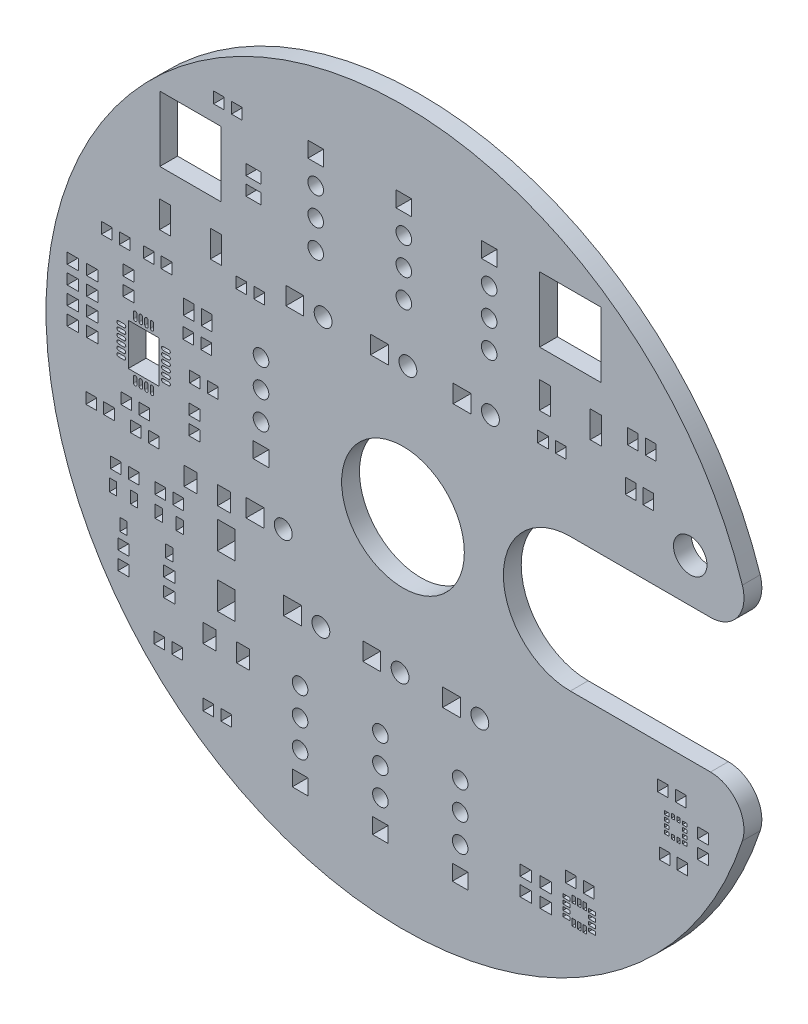
SolidWorks part; units mm, degrees
ref_plane "Plan de face" through (0, 0, 0) normal (0, 0, 1) x (1, 0, 0)
ref_plane "Plan de dessus" through (0, 0, 0) normal (0, 1, 0) x (1, 0, 0)
ref_plane "Plan de droite" through (0, 0, 0) normal (1, 0, 0) x (0, 0, -1)
sketch "Model" plane through (0, 0, 0) normal (0, 0, 1) x (1, 0, 0)
  line L0 (25.45, -12.55) -> (25.45, -12.85)
  line L1 (25.45, -12.85) -> (25.05, -12.85)
  line L2 (25.05, -12.85) -> (25.05, -12.55)
  line L3 (25.05, -12.55) -> (25.45, -12.55)
  line L4 (25.45, -12.05) -> (25.45, -12.35)
  line L5 (25.45, -12.35) -> (25.05, -12.35)
  line L6 (25.05, -12.35) -> (25.05, -12.05)
  line L7 (25.05, -12.05) -> (25.45, -12.05)
  line L8 (25.45, -11.55) -> (25.45, -11.85)
  line L9 (25.45, -11.85) -> (25.05, -11.85)
  line L10 (25.05, -11.85) -> (25.05, -11.55)
  line L11 (25.05, -11.55) -> (25.45, -11.55)
  line L12 (25.45, -11.05) -> (25.45, -11.35)
  line L13 (25.45, -11.35) -> (25.05, -11.35)
  line L14 (25.05, -11.35) -> (25.05, -11.05)
  line L15 (25.05, -11.05) -> (25.45, -11.05)
  line L16 (24.55, -10.95) -> (24.85, -10.95)
  line L17 (24.85, -10.95) -> (24.85, -11.35)
  line L18 (24.85, -11.35) -> (24.55, -11.35)
  line L19 (24.55, -11.35) -> (24.55, -10.95)
  line L20 (24.05, -10.95) -> (24.35, -10.95)
  line L21 (24.35, -10.95) -> (24.35, -11.35)
  line L22 (24.35, -11.35) -> (24.05, -11.35)
  line L23 (24.05, -11.35) -> (24.05, -10.95)
  line L24 (23.85, -11.05) -> (23.85, -11.35)
  line L25 (23.85, -11.35) -> (23.45, -11.35)
  line L26 (23.45, -11.35) -> (23.45, -11.05)
  line L27 (23.45, -11.05) -> (23.85, -11.05)
  line L28 (23.85, -11.55) -> (23.85, -11.85)
  line L29 (23.85, -11.85) -> (23.45, -11.85)
  line L30 (23.45, -11.85) -> (23.45, -11.55)
  line L31 (23.45, -11.55) -> (23.85, -11.55)
  line L32 (23.85, -12.05) -> (23.85, -12.35)
  line L33 (23.85, -12.35) -> (23.45, -12.35)
  line L34 (23.45, -12.35) -> (23.45, -12.05)
  line L35 (23.45, -12.05) -> (23.85, -12.05)
  line L36 (23.85, -12.55) -> (23.85, -12.85)
  line L37 (23.85, -12.85) -> (23.45, -12.85)
  line L38 (23.45, -12.85) -> (23.45, -12.55)
  line L39 (23.45, -12.55) -> (23.85, -12.55)
  line L40 (24.05, -12.55) -> (24.35, -12.55)
  line L41 (24.35, -12.55) -> (24.35, -12.95)
  line L42 (24.35, -12.95) -> (24.05, -12.95)
  line L43 (24.05, -12.95) -> (24.05, -12.55)
  line L44 (24.55, -12.55) -> (24.85, -12.55)
  line L45 (24.85, -12.55) -> (24.85, -12.95)
  line L46 (24.85, -12.95) -> (24.55, -12.95)
  line L47 (24.55, -12.95) -> (24.55, -12.55)
  line L48 (17.25, -23.55) -> (17.25, -23.85)
  line L49 (17.25, -23.85) -> (16.65, -23.85)
  line L50 (16.65, -23.85) -> (16.65, -23.55)
  line L51 (16.65, -23.55) -> (17.25, -23.55)
  line L52 (17.25, -23.05) -> (17.25, -23.35)
  line L53 (17.25, -23.35) -> (16.65, -23.35)
  line L54 (16.65, -23.35) -> (16.65, -23.05)
  line L55 (16.65, -23.05) -> (17.25, -23.05)
  line L56 (17.25, -22.55) -> (17.25, -22.85)
  line L57 (17.25, -22.85) -> (16.65, -22.85)
  line L58 (16.65, -22.85) -> (16.65, -22.55)
  line L59 (16.65, -22.55) -> (17.25, -22.55)
  line L60 (17.25, -22.05) -> (17.25, -22.35)
  line L61 (17.25, -22.35) -> (16.65, -22.35)
  line L62 (16.65, -22.35) -> (16.65, -22.05)
  line L63 (16.65, -22.05) -> (17.25, -22.05)
  line L64 (16.15, -21.75) -> (16.45, -21.75)
  line L65 (16.45, -21.75) -> (16.45, -22.35)
  line L66 (16.45, -22.35) -> (16.15, -22.35)
  line L67 (16.15, -22.35) -> (16.15, -21.75)
  line L68 (15.65, -21.75) -> (15.95, -21.75)
  line L69 (15.95, -21.75) -> (15.95, -22.35)
  line L70 (15.95, -22.35) -> (15.65, -22.35)
  line L71 (15.65, -22.35) -> (15.65, -21.75)
  line L72 (15.15, -21.75) -> (15.45, -21.75)
  line L73 (15.45, -21.75) -> (15.45, -22.35)
  line L74 (15.45, -22.35) -> (15.15, -22.35)
  line L75 (15.15, -22.35) -> (15.15, -21.75)
  line L76 (14.95, -22.05) -> (14.95, -22.35)
  line L77 (14.95, -22.35) -> (14.35, -22.35)
  line L78 (14.35, -22.35) -> (14.35, -22.05)
  line L79 (14.35, -22.05) -> (14.95, -22.05)
  line L80 (14.95, -22.55) -> (14.95, -22.85)
  line L81 (14.95, -22.85) -> (14.35, -22.85)
  line L82 (14.35, -22.85) -> (14.35, -22.55)
  line L83 (14.35, -22.55) -> (14.95, -22.55)
  line L84 (14.95, -23.05) -> (14.95, -23.35)
  line L85 (14.95, -23.35) -> (14.35, -23.35)
  line L86 (14.35, -23.35) -> (14.35, -23.05)
  line L87 (14.35, -23.05) -> (14.95, -23.05)
  line L88 (14.95, -23.55) -> (14.95, -23.85)
  line L89 (14.95, -23.85) -> (14.35, -23.85)
  line L90 (14.35, -23.85) -> (14.35, -23.55)
  line L91 (14.35, -23.55) -> (14.95, -23.55)
  line L92 (15.15, -23.55) -> (15.45, -23.55)
  line L93 (15.45, -23.55) -> (15.45, -24.15)
  line L94 (15.45, -24.15) -> (15.15, -24.15)
  line L95 (15.15, -24.15) -> (15.15, -23.55)
  line L96 (15.65, -23.55) -> (15.95, -23.55)
  line L97 (15.95, -23.55) -> (15.95, -24.15)
  line L98 (15.95, -24.15) -> (15.65, -24.15)
  line L99 (15.65, -24.15) -> (15.65, -23.55)
  line L100 (16.15, -23.55) -> (16.45, -23.55)
  line L101 (16.45, -23.55) -> (16.45, -24.15)
  line L102 (16.45, -24.15) -> (16.15, -24.15)
  line L103 (16.15, -24.15) -> (16.15, -23.55)
  line L104 (-18.075, 7.175) -> (-17.125, 7.175)
  line L105 (-17.125, 7.175) -> (-17.125, 5.825)
  line L106 (-17.125, 5.825) -> (-18.075, 5.825)
  line L107 (-18.075, 5.825) -> (-18.075, 7.175)
  line L108 (-19.675, 7.175) -> (-18.725, 7.175)
  line L109 (-18.725, 7.175) -> (-18.725, 5.825)
  line L110 (-18.725, 5.825) -> (-19.675, 5.825)
  line L111 (-19.675, 5.825) -> (-19.675, 7.175)
  line L112 (-21.5, 0) -> (-21, 0)
  line L113 (-21, -0.3) -> (-21.5, -0.3)
  line L114 (-21.5, 0.5) -> (-21, 0.5)
  line L115 (-21, 0.2) -> (-21.5, 0.2)
  line L116 (-21.5, 1) -> (-21, 1)
  line L117 (-21, 0.7) -> (-21.5, 0.7)
  line L118 (-21.5, 1.5) -> (-21, 1.5)
  line L119 (-21, 1.2) -> (-21.5, 1.2)
  line L120 (-21.5, 2) -> (-21, 2)
  line L121 (-21, 1.7) -> (-21.5, 1.7)
  line L122 (-21.5, 2.5) -> (-21, 2.5)
  line L123 (-21, 2.2) -> (-21.5, 2.2)
  line L124 (-22.65, 3.35) -> (-22.65, 3.85)
  line L125 (-22.35, 3.85) -> (-22.35, 3.35)
  line L126 (-23.15, 3.35) -> (-23.15, 3.85)
  line L127 (-22.85, 3.85) -> (-22.85, 3.35)
  line L128 (-23.65, 3.35) -> (-23.65, 3.85)
  line L129 (-23.35, 3.85) -> (-23.35, 3.35)
  line L130 (-24.15, 3.35) -> (-24.15, 3.85)
  line L131 (-23.85, 3.85) -> (-23.85, 3.35)
  line L132 (-25.5, 2.5) -> (-25, 2.5)
  line L133 (-25, 2.2) -> (-25.5, 2.2)
  line L134 (-25.5, 2) -> (-25, 2)
  line L135 (-25, 1.7) -> (-25.5, 1.7)
  line L136 (-25.5, 1.5) -> (-25, 1.5)
  line L137 (-25, 1.2) -> (-25.5, 1.2)
  line L138 (-25.5, 1) -> (-25, 1)
  line L139 (-25, 0.7) -> (-25.5, 0.7)
  line L140 (-25.5, 0.5) -> (-25, 0.5)
  line L141 (-25, 0.2) -> (-25.5, 0.2)
  line L142 (-25.5, 0) -> (-25, 0)
  line L143 (-25, -0.3) -> (-25.5, -0.3)
  line L144 (-24.15, -1.65) -> (-24.15, -1.15)
  line L145 (-23.85, -1.15) -> (-23.85, -1.65)
  line L146 (-23.65, -1.65) -> (-23.65, -1.15)
  line L147 (-23.35, -1.15) -> (-23.35, -1.65)
  line L148 (-23.15, -1.65) -> (-23.15, -1.15)
  line L149 (-22.85, -1.15) -> (-22.85, -1.65)
  line L150 (-22.65, -1.65) -> (-22.65, -1.15)
  line L151 (-22.35, -1.15) -> (-22.35, -1.65)
  line L152 (-21.875, 2.975) -> (-21.875, -0.775)
  line L153 (-21.875, -0.775) -> (-24.625, -0.775)
  line L154 (-24.625, -0.775) -> (-24.625, 2.975)
  line L155 (-24.625, 2.975) -> (-21.875, 2.975)
  line L156 (-24.425, -10.1) -> (-23.775, -10.1)
  line L157 (-23.775, -10.1) -> (-23.775, -11.2)
  line L158 (-23.775, -11.2) -> (-24.425, -11.2)
  line L159 (-24.425, -11.2) -> (-24.425, -10.1)
  line L160 (-26.325, -10.1) -> (-25.675, -10.1)
  line L161 (-25.675, -10.1) -> (-25.675, -11.2)
  line L162 (-25.675, -11.2) -> (-26.325, -11.2)
  line L163 (-26.325, -11.2) -> (-26.325, -10.1)
  line L164 (-25.375, -12.7) -> (-24.725, -12.7)
  line L165 (-24.725, -12.7) -> (-24.725, -13.8)
  line L166 (-24.725, -13.8) -> (-25.375, -13.8)
  line L167 (-25.375, -13.8) -> (-25.375, -12.7)
  line L168 (-20.325, -10.1) -> (-19.675, -10.1)
  line L169 (-19.675, -10.1) -> (-19.675, -11.2)
  line L170 (-19.675, -11.2) -> (-20.325, -11.2)
  line L171 (-20.325, -11.2) -> (-20.325, -10.1)
  line L172 (-22.225, -10.1) -> (-21.575, -10.1)
  line L173 (-21.575, -10.1) -> (-21.575, -11.2)
  line L174 (-21.575, -11.2) -> (-22.225, -11.2)
  line L175 (-22.225, -11.2) -> (-22.225, -10.1)
  line L176 (-21.275, -12.7) -> (-20.625, -12.7)
  line L177 (-20.625, -12.7) -> (-20.625, -13.8)
  line L178 (-20.625, -13.8) -> (-21.275, -13.8)
  line L179 (-21.275, -13.8) -> (-21.275, -12.7)
  line L180 (21.525, 13.075) -> (22.475, 13.075)
  line L181 (22.475, 13.075) -> (22.475, 11.725)
  line L182 (22.475, 11.725) -> (21.525, 11.725)
  line L183 (21.525, 11.725) -> (21.525, 13.075)
  line L184 (19.925, 13.075) -> (20.875, 13.075)
  line L185 (20.875, 13.075) -> (20.875, 11.725)
  line L186 (20.875, 11.725) -> (19.925, 11.725)
  line L187 (19.925, 11.725) -> (19.925, 13.075)
  line L188 (-14.075, 19.475) -> (-14.075, 20.425)
  line L189 (-14.075, 20.425) -> (-12.725, 20.425)
  line L190 (-12.725, 20.425) -> (-12.725, 19.475)
  line L191 (-12.725, 19.475) -> (-14.075, 19.475)
  line L192 (-14.075, 17.875) -> (-14.075, 18.825)
  line L193 (-14.075, 18.825) -> (-12.725, 18.825)
  line L194 (-12.725, 18.825) -> (-12.725, 17.875)
  line L195 (-12.725, 17.875) -> (-14.075, 17.875)
  line L196 (21.075, 15.675) -> (20.125, 15.675)
  line L197 (20.125, 15.675) -> (20.125, 17.025)
  line L198 (20.125, 17.025) -> (21.075, 17.025)
  line L199 (21.075, 17.025) -> (21.075, 15.675)
  line L200 (22.675, 15.675) -> (21.725, 15.675)
  line L201 (21.725, 15.675) -> (21.725, 17.025)
  line L202 (21.725, 17.025) -> (22.675, 17.025)
  line L203 (22.675, 17.025) -> (22.675, 15.675)
  line L204 (-20.83, 11.4) -> (-21.83, 11.4)
  line L205 (-21.83, 11.4) -> (-21.83, 13.8)
  line L206 (-21.83, 13.8) -> (-20.83, 13.8)
  line L207 (-20.83, 13.8) -> (-20.83, 11.4)
  line L208 (-16.27, 11.4) -> (-17.27, 11.4)
  line L209 (-17.27, 11.4) -> (-17.27, 13.8)
  line L210 (-17.27, 13.8) -> (-16.27, 13.8)
  line L211 (-16.27, 13.8) -> (-16.27, 11.4)
  line L212 (-16.3, 16.325) -> (-21.8, 16.325)
  line L213 (-21.8, 16.325) -> (-21.8, 22.175)
  line L214 (-21.8, 22.175) -> (-16.3, 22.175)
  line L215 (-16.3, 22.175) -> (-16.3, 16.325)
  line L216 (13.22, 14.4) -> (12.22, 14.4)
  line L217 (12.22, 14.4) -> (12.22, 16.8)
  line L218 (12.22, 16.8) -> (13.22, 16.8)
  line L219 (13.22, 16.8) -> (13.22, 14.4)
  line L220 (17.78, 14.4) -> (16.78, 14.4)
  line L221 (16.78, 14.4) -> (16.78, 16.8)
  line L222 (16.78, 16.8) -> (17.78, 16.8)
  line L223 (17.78, 16.8) -> (17.78, 14.4)
  line L224 (17.75, 19.325) -> (12.25, 19.325)
  line L225 (12.25, 19.325) -> (12.25, 25.175)
  line L226 (12.25, 25.175) -> (17.75, 25.175)
  line L227 (17.75, 25.175) -> (17.75, 19.325)
  line L228 (-16.025, 23.6) -> (-16.975, 23.6)
  line L229 (-16.975, 23.6) -> (-16.975, 24.6)
  line L230 (-16.975, 24.6) -> (-16.025, 24.6)
  line L231 (-16.025, 24.6) -> (-16.025, 23.6)
  line L232 (-14.425, 23.6) -> (-15.375, 23.6)
  line L233 (-15.375, 23.6) -> (-15.375, 24.6)
  line L234 (-15.375, 24.6) -> (-14.425, 24.6)
  line L235 (-14.425, 24.6) -> (-14.425, 23.6)
  line L236 (-20.725, -20) -> (-19.775, -20)
  line L237 (-19.775, -20) -> (-19.775, -21)
  line L238 (-19.775, -21) -> (-20.725, -21)
  line L239 (-20.725, -21) -> (-20.725, -20)
  line L240 (-22.325, -20) -> (-21.375, -20)
  line L241 (-21.375, -20) -> (-21.375, -21)
  line L242 (-21.375, -21) -> (-22.325, -21)
  line L243 (-22.325, -21) -> (-22.325, -20)
  line L244 (-16.975, -24) -> (-17.925, -24)
  line L245 (-17.925, -24) -> (-17.925, -23)
  line L246 (-17.925, -23) -> (-16.975, -23)
  line L247 (-16.975, -23) -> (-16.975, -24)
  line L248 (-15.375, -24) -> (-16.325, -24)
  line L249 (-16.325, -24) -> (-16.325, -23)
  line L250 (-16.325, -23) -> (-15.375, -23)
  line L251 (-15.375, -23) -> (-15.375, -24)
  line L252 (-14.025, 10.25) -> (-14.975, 10.25)
  line L253 (-14.975, 10.25) -> (-14.975, 11.25)
  line L254 (-14.975, 11.25) -> (-14.025, 11.25)
  line L255 (-14.025, 11.25) -> (-14.025, 10.25)
  line L256 (-12.425, 10.25) -> (-13.375, 10.25)
  line L257 (-13.375, 10.25) -> (-13.375, 11.25)
  line L258 (-13.375, 11.25) -> (-12.425, 11.25)
  line L259 (-12.425, 11.25) -> (-12.425, 10.25)
  line L260 (23.775, -9.9) -> (22.825, -9.9)
  line L261 (22.825, -9.9) -> (22.825, -8.9)
  line L262 (22.825, -8.9) -> (23.775, -8.9)
  line L263 (23.775, -8.9) -> (23.775, -9.9)
  line L264 (25.375, -9.9) -> (24.425, -9.9)
  line L265 (24.425, -9.9) -> (24.425, -8.9)
  line L266 (24.425, -8.9) -> (25.375, -8.9)
  line L267 (25.375, -8.9) -> (25.375, -9.9)
  line L268 (24.575, -14.1) -> (25.525, -14.1)
  line L269 (25.525, -14.1) -> (25.525, -15.1)
  line L270 (25.525, -15.1) -> (24.575, -15.1)
  line L271 (24.575, -15.1) -> (24.575, -14.1)
  line L272 (22.975, -14.1) -> (23.925, -14.1)
  line L273 (23.925, -14.1) -> (23.925, -15.1)
  line L274 (23.925, -15.1) -> (22.975, -15.1)
  line L275 (22.975, -15.1) -> (22.975, -14.1)
  line L276 (27.4, -12.425) -> (27.4, -13.375)
  line L277 (27.4, -13.375) -> (26.4, -13.375)
  line L278 (26.4, -13.375) -> (26.4, -12.425)
  line L279 (26.4, -12.425) -> (27.4, -12.425)
  line L280 (27.4, -10.825) -> (27.4, -11.775)
  line L281 (27.4, -11.775) -> (26.4, -11.775)
  line L282 (26.4, -11.775) -> (26.4, -10.825)
  line L283 (26.4, -10.825) -> (27.4, -10.825)
  line L284 (15.525, -21.1) -> (14.575, -21.1)
  line L285 (14.575, -21.1) -> (14.575, -20.1)
  line L286 (14.575, -20.1) -> (15.525, -20.1)
  line L287 (15.525, -20.1) -> (15.525, -21.1)
  line L288 (17.125, -21.1) -> (16.175, -21.1)
  line L289 (16.175, -21.1) -> (16.175, -20.1)
  line L290 (16.175, -20.1) -> (17.125, -20.1)
  line L291 (17.125, -20.1) -> (17.125, -21.1)
  line L292 (11.5, -23.275) -> (11.5, -24.225)
  line L293 (11.5, -24.225) -> (10.5, -24.225)
  line L294 (10.5, -24.225) -> (10.5, -23.275)
  line L295 (10.5, -23.275) -> (11.5, -23.275)
  line L296 (11.5, -21.675) -> (11.5, -22.625)
  line L297 (11.5, -22.625) -> (10.5, -22.625)
  line L298 (10.5, -22.625) -> (10.5, -21.675)
  line L299 (10.5, -21.675) -> (11.5, -21.675)
  line L300 (13.3, -23.275) -> (13.3, -24.225)
  line L301 (13.3, -24.225) -> (12.3, -24.225)
  line L302 (12.3, -24.225) -> (12.3, -23.275)
  line L303 (12.3, -23.275) -> (13.3, -23.275)
  line L304 (13.3, -21.675) -> (13.3, -22.625)
  line L305 (13.3, -22.625) -> (12.3, -22.625)
  line L306 (12.3, -22.625) -> (12.3, -21.675)
  line L307 (12.3, -21.675) -> (13.3, -21.675)
  line L308 (-18.775, 3.95) -> (-19.725, 3.95)
  line L309 (-19.725, 3.95) -> (-19.725, 4.95)
  line L310 (-19.725, 4.95) -> (-18.775, 4.95)
  line L311 (-18.775, 4.95) -> (-18.775, 3.95)
  line L312 (-17.175, 3.95) -> (-18.125, 3.95)
  line L313 (-18.125, 3.95) -> (-18.125, 4.95)
  line L314 (-18.125, 4.95) -> (-17.175, 4.95)
  line L315 (-17.175, 4.95) -> (-17.175, 3.95)
  line L316 (-23.675, -2.9) -> (-22.725, -2.9)
  line L317 (-22.725, -2.9) -> (-22.725, -3.9)
  line L318 (-22.725, -3.9) -> (-23.675, -3.9)
  line L319 (-23.675, -3.9) -> (-23.675, -2.9)
  line L320 (-25.275, -2.9) -> (-24.325, -2.9)
  line L321 (-24.325, -2.9) -> (-24.325, -3.9)
  line L322 (-24.325, -3.9) -> (-25.275, -3.9)
  line L323 (-25.275, -3.9) -> (-25.275, -2.9)
  line L324 (-26.825, -4.45) -> (-25.875, -4.45)
  line L325 (-25.875, -4.45) -> (-25.875, -5.45)
  line L326 (-25.875, -5.45) -> (-26.825, -5.45)
  line L327 (-26.825, -5.45) -> (-26.825, -4.45)
  line L328 (-28.425, -4.45) -> (-27.475, -4.45)
  line L329 (-27.475, -4.45) -> (-27.475, -5.45)
  line L330 (-27.475, -5.45) -> (-28.425, -5.45)
  line L331 (-28.425, -5.45) -> (-28.425, -4.45)
  line L332 (-25.1, 6.175) -> (-25.1, 7.125)
  line L333 (-25.1, 7.125) -> (-24.1, 7.125)
  line L334 (-24.1, 7.125) -> (-24.1, 6.175)
  line L335 (-24.1, 6.175) -> (-25.1, 6.175)
  line L336 (-25.1, 4.575) -> (-25.1, 5.525)
  line L337 (-25.1, 5.525) -> (-24.1, 5.525)
  line L338 (-24.1, 5.525) -> (-24.1, 4.575)
  line L339 (-24.1, 4.575) -> (-25.1, 4.575)
  line L340 (-17.525, 1.85) -> (-16.575, 1.85)
  line L341 (-16.575, 1.85) -> (-16.575, 0.85)
  line L342 (-16.575, 0.85) -> (-17.525, 0.85)
  line L343 (-17.525, 0.85) -> (-17.525, 1.85)
  line L344 (-19.125, 1.85) -> (-18.175, 1.85)
  line L345 (-18.175, 1.85) -> (-18.175, 0.85)
  line L346 (-18.175, 0.85) -> (-19.125, 0.85)
  line L347 (-19.125, 0.85) -> (-19.125, 1.85)
  line L348 (-18.2, -2.325) -> (-18.2, -3.275)
  line L349 (-18.2, -3.275) -> (-19.2, -3.275)
  line L350 (-19.2, -3.275) -> (-19.2, -2.325)
  line L351 (-19.2, -2.325) -> (-18.2, -2.325)
  line L352 (-18.2, -0.725) -> (-18.2, -1.675)
  line L353 (-18.2, -1.675) -> (-19.2, -1.675)
  line L354 (-19.2, -1.675) -> (-19.2, -0.725)
  line L355 (-19.2, -0.725) -> (-18.2, -0.725)
  line L356 (-22.825, -4.65) -> (-21.875, -4.65)
  line L357 (-21.875, -4.65) -> (-21.875, -5.65)
  line L358 (-21.875, -5.65) -> (-22.825, -5.65)
  line L359 (-22.825, -5.65) -> (-22.825, -4.65)
  line L360 (-24.425, -4.65) -> (-23.475, -4.65)
  line L361 (-23.475, -4.65) -> (-23.475, -5.65)
  line L362 (-23.475, -5.65) -> (-24.425, -5.65)
  line L363 (-24.425, -5.65) -> (-24.425, -4.65)
  line L364 (-29.1, 0.725) -> (-29.1, -0.225)
  line L365 (-29.1, -0.225) -> (-30.1, -0.225)
  line L366 (-30.1, -0.225) -> (-30.1, 0.725)
  line L367 (-30.1, 0.725) -> (-29.1, 0.725)
  line L368 (-29.1, 2.325) -> (-29.1, 1.375)
  line L369 (-29.1, 1.375) -> (-30.1, 1.375)
  line L370 (-30.1, 1.375) -> (-30.1, 2.325)
  line L371 (-30.1, 2.325) -> (-29.1, 2.325)
  line L372 (-27.35, 0.725) -> (-27.35, -0.225)
  line L373 (-27.35, -0.225) -> (-28.35, -0.225)
  line L374 (-28.35, -0.225) -> (-28.35, 0.725)
  line L375 (-28.35, 0.725) -> (-27.35, 0.725)
  line L376 (-27.35, 2.325) -> (-27.35, 1.375)
  line L377 (-27.35, 1.375) -> (-28.35, 1.375)
  line L378 (-28.35, 1.375) -> (-28.35, 2.325)
  line L379 (-28.35, 2.325) -> (-27.35, 2.325)
  line L380 (-29.1, 3.925) -> (-29.1, 2.975)
  line L381 (-29.1, 2.975) -> (-30.1, 2.975)
  line L382 (-30.1, 2.975) -> (-30.1, 3.925)
  line L383 (-30.1, 3.925) -> (-29.1, 3.925)
  line L384 (-29.1, 5.525) -> (-29.1, 4.575)
  line L385 (-29.1, 4.575) -> (-30.1, 4.575)
  line L386 (-30.1, 4.575) -> (-30.1, 5.525)
  line L387 (-30.1, 5.525) -> (-29.1, 5.525)
  line L388 (-27.35, 3.925) -> (-27.35, 2.975)
  line L389 (-27.35, 2.975) -> (-28.35, 2.975)
  line L390 (-28.35, 2.975) -> (-28.35, 3.925)
  line L391 (-28.35, 3.925) -> (-27.35, 3.925)
  line L392 (-27.35, 5.525) -> (-27.35, 4.575)
  line L393 (-27.35, 4.575) -> (-28.35, 4.575)
  line L394 (-28.35, 4.575) -> (-28.35, 5.525)
  line L395 (-28.35, 5.525) -> (-27.35, 5.525)
  line L396 (-22.325, 8.45) -> (-23.275, 8.45)
  line L397 (-23.275, 8.45) -> (-23.275, 9.45)
  line L398 (-23.275, 9.45) -> (-22.325, 9.45)
  line L399 (-22.325, 9.45) -> (-22.325, 8.45)
  line L400 (-20.725, 8.45) -> (-21.675, 8.45)
  line L401 (-21.675, 8.45) -> (-21.675, 9.45)
  line L402 (-21.675, 9.45) -> (-20.725, 9.45)
  line L403 (-20.725, 9.45) -> (-20.725, 8.45)
  line L404 (-26.075, 8.45) -> (-27.025, 8.45)
  line L405 (-27.025, 8.45) -> (-27.025, 9.45)
  line L406 (-27.025, 9.45) -> (-26.075, 9.45)
  line L407 (-26.075, 9.45) -> (-26.075, 8.45)
  line L408 (-24.475, 8.45) -> (-25.425, 8.45)
  line L409 (-25.425, 8.45) -> (-25.425, 9.45)
  line L410 (-25.425, 9.45) -> (-24.475, 9.45)
  line L411 (-24.475, 9.45) -> (-24.475, 8.45)
  line L412 (-24.625, -8.35) -> (-23.675, -8.35)
  line L413 (-23.675, -8.35) -> (-23.675, -9.35)
  line L414 (-23.675, -9.35) -> (-24.625, -9.35)
  line L415 (-24.625, -9.35) -> (-24.625, -8.35)
  line L416 (-26.225, -8.35) -> (-25.275, -8.35)
  line L417 (-25.275, -8.35) -> (-25.275, -9.35)
  line L418 (-25.275, -9.35) -> (-26.225, -9.35)
  line L419 (-26.225, -9.35) -> (-26.225, -8.35)
  line L420 (-24.55, -15.975) -> (-24.55, -16.925)
  line L421 (-24.55, -16.925) -> (-25.55, -16.925)
  line L422 (-25.55, -16.925) -> (-25.55, -15.975)
  line L423 (-25.55, -15.975) -> (-24.55, -15.975)
  line L424 (-24.55, -14.375) -> (-24.55, -15.325)
  line L425 (-24.55, -15.325) -> (-25.55, -15.325)
  line L426 (-25.55, -15.325) -> (-25.55, -14.375)
  line L427 (-25.55, -14.375) -> (-24.55, -14.375)
  line L428 (-20.625, -8.35) -> (-19.675, -8.35)
  line L429 (-19.675, -8.35) -> (-19.675, -9.35)
  line L430 (-19.675, -9.35) -> (-20.625, -9.35)
  line L431 (-20.625, -9.35) -> (-20.625, -8.35)
  line L432 (-22.225, -8.35) -> (-21.275, -8.35)
  line L433 (-21.275, -8.35) -> (-21.275, -9.35)
  line L434 (-21.275, -9.35) -> (-22.225, -9.35)
  line L435 (-22.225, -9.35) -> (-22.225, -8.35)
  line L436 (-20.45, -16.025) -> (-20.45, -16.975)
  line L437 (-20.45, -16.975) -> (-21.45, -16.975)
  line L438 (-21.45, -16.975) -> (-21.45, -16.025)
  line L439 (-21.45, -16.025) -> (-20.45, -16.025)
  line L440 (-20.45, -14.425) -> (-20.45, -15.375)
  line L441 (-20.45, -15.375) -> (-21.45, -15.375)
  line L442 (-21.45, -15.375) -> (-21.45, -14.425)
  line L443 (-21.45, -14.425) -> (-20.45, -14.425)
  line L444 (13.675, 12.8) -> (14.625, 12.8)
  line L445 (14.625, 12.8) -> (14.625, 11.8)
  line L446 (14.625, 11.8) -> (13.675, 11.8)
  line L447 (13.675, 11.8) -> (13.675, 12.8)
  line L448 (12.075, 12.8) -> (13.025, 12.8)
  line L449 (13.025, 12.8) -> (13.025, 11.8)
  line L450 (13.025, 11.8) -> (12.075, 11.8)
  line L451 (12.075, 11.8) -> (12.075, 12.8)
  line L452 (-16.775, -18.775) -> (-17.925, -18.775)
  line L453 (-17.925, -18.775) -> (-17.925, -17.125)
  line L454 (-17.925, -17.125) -> (-16.775, -17.125)
  line L455 (-16.775, -17.125) -> (-16.775, -18.775)
  line L456 (-13.775, -18.775) -> (-14.925, -18.775)
  line L457 (-14.925, -18.775) -> (-14.925, -17.125)
  line L458 (-14.925, -17.125) -> (-13.775, -17.125)
  line L459 (-13.775, -17.125) -> (-13.775, -18.775)
  line L460 (-18.475, -7.425) -> (-19.625, -7.425)
  line L461 (-19.625, -7.425) -> (-19.625, -5.775)
  line L462 (-19.625, -5.775) -> (-18.475, -5.775)
  line L463 (-18.475, -5.775) -> (-18.475, -7.425)
  line L464 (-15.475, -7.425) -> (-16.625, -7.425)
  line L465 (-16.625, -7.425) -> (-16.625, -5.775)
  line L466 (-16.625, -5.775) -> (-15.475, -5.775)
  line L467 (-15.475, -5.775) -> (-15.475, -7.425)
  line L468 (-16.625, -8.475) -> (-15.075, -8.475)
  line L469 (-15.075, -8.475) -> (-15.075, -10.925)
  line L470 (-15.075, -10.925) -> (-16.625, -10.925)
  line L471 (-16.625, -10.925) -> (-16.625, -8.475)
  line L472 (-16.625, -13.175) -> (-15.075, -13.175)
  line L473 (-15.075, -13.175) -> (-15.075, -15.625)
  line L474 (-15.075, -15.625) -> (-16.625, -15.625)
  line L475 (-16.625, -15.625) -> (-16.625, -13.175)
  line L476 (-12.025, -2.175) -> (-13.425, -2.175)
  line L477 (-13.425, -2.175) -> (-13.425, -0.775)
  line L478 (-13.425, -0.775) -> (-12.025, -0.775)
  line L479 (-12.025, -0.775) -> (-12.025, -2.175)
  line L480 (-8.525, -25.9) -> (-9.925, -25.9)
  line L481 (-9.925, -25.9) -> (-9.925, -24.5)
  line L482 (-9.925, -24.5) -> (-8.525, -24.5)
  line L483 (-8.525, -24.5) -> (-8.525, -25.9)
  line L484 (5.825, -26.05) -> (4.425, -26.05)
  line L485 (4.425, -26.05) -> (4.425, -24.65)
  line L486 (4.425, -24.65) -> (5.825, -24.65)
  line L487 (5.825, -24.65) -> (5.825, -26.05)
  line L488 (-1.325, -26.0001) -> (-2.725, -26.0001)
  line L489 (-2.725, -26.0001) -> (-2.725, -24.6001)
  line L490 (-2.725, -24.6001) -> (-1.325, -24.6001)
  line L491 (-1.325, -24.6001) -> (-1.325, -26.0001)
  line L492 (-8.525, 24.9999) -> (-7.125, 24.9999)
  line L493 (-7.125, 24.9999) -> (-7.125, 23.5999)
  line L494 (-7.125, 23.5999) -> (-8.525, 23.5999)
  line L495 (-8.525, 23.5999) -> (-8.525, 24.9999)
  line L496 (7.025, 25) -> (8.425, 25)
  line L497 (8.425, 25) -> (8.425, 23.6)
  line L498 (8.425, 23.6) -> (7.025, 23.6)
  line L499 (7.025, 23.6) -> (7.025, 25)
  line L500 (-0.625, 25.1) -> (0.775, 25.1)
  line L501 (0.775, 25.1) -> (0.775, 23.7)
  line L502 (0.775, 23.7) -> (-0.625, 23.7)
  line L503 (-0.625, 23.7) -> (-0.625, 25.1)
  line L504 (3.55, -13) -> (3.55, -11.4)
  line L505 (3.55, -11.4) -> (5.15, -11.4)
  line L506 (5.15, -11.4) -> (5.15, -13)
  line L507 (5.15, -13) -> (3.55, -13)
  line L508 (-3.6, -13) -> (-3.6, -11.4)
  line L509 (-3.6, -11.4) -> (-2, -11.4)
  line L510 (-2, -11.4) -> (-2, -13)
  line L511 (-2, -13) -> (-3.6, -13)
  line L512 (-10.7, -13) -> (-10.7, -11.4)
  line L513 (-10.7, -11.4) -> (-9.1, -11.4)
  line L514 (-9.1, -11.4) -> (-9.1, -13)
  line L515 (-9.1, -13) -> (-10.7, -13)
  line L516 (-10.5, 11.15) -> (-10.5, 12.75)
  line L517 (-10.5, 12.75) -> (-8.9, 12.75)
  line L518 (-8.9, 12.75) -> (-8.9, 11.15)
  line L519 (-8.9, 11.15) -> (-10.5, 11.15)
  line L520 (-2.9, 11.15) -> (-2.9, 12.75)
  line L521 (-2.9, 12.75) -> (-1.3, 12.75)
  line L522 (-1.3, 12.75) -> (-1.3, 11.15)
  line L523 (-1.3, 11.15) -> (-2.9, 11.15)
  line L524 (4.5, 11.05) -> (4.5, 12.65)
  line L525 (4.5, 12.65) -> (6.1, 12.65)
  line L526 (6.1, 12.65) -> (6.1, 11.05)
  line L527 (6.1, 11.05) -> (4.5, 11.05)
  line L528 (-14.07, -7.1) -> (-14.07, -5.5)
  line L529 (-14.07, -5.5) -> (-12.47, -5.5)
  line L530 (-12.47, -5.5) -> (-12.47, -7.1)
  line L531 (-12.47, -7.1) -> (-14.07, -7.1)
  line L532 (27.5681, -6) -> (15, -6)
  line L533 (15, 6) -> (27.5681, 6)
  circle A0 centre (25.75, 9.9) radius 1.5
  circle A1 centre (-12.725, 1.025) radius 0.7
  circle A2 centre (-12.725, 3.525) radius 0.7
  circle A3 centre (-12.725, 6.025) radius 0.7
  circle A4 centre (-9.225, -22.7) radius 0.7
  circle A5 centre (-9.225, -20.2) radius 0.7
  circle A6 centre (-9.225, -17.7) radius 0.7
  circle A7 centre (5.125, -22.85) radius 0.7
  circle A8 centre (5.125, -20.35) radius 0.7
  circle A9 centre (5.125, -17.85) radius 0.7
  circle A10 centre (-2.025, -22.8001) radius 0.7
  circle A11 centre (-2.025, -20.3001) radius 0.7
  circle A12 centre (-2.025, -17.8001) radius 0.7
  circle A13 centre (-7.825, 21.7999) radius 0.7
  circle A14 centre (-7.825, 19.2999) radius 0.7
  circle A15 centre (-7.825, 16.7999) radius 0.7
  circle A16 centre (7.725, 21.8) radius 0.7
  circle A17 centre (7.725, 19.3) radius 0.7
  circle A18 centre (7.725, 16.8) radius 0.7
  circle A19 centre (0.075, 21.9) radius 0.7
  circle A20 centre (0.075, 19.4) radius 0.7
  circle A21 centre (0.075, 16.9) radius 0.7
  circle A22 centre (6.89, -12.2) radius 0.8
  circle A23 centre (-0.26, -12.2) radius 0.8
  circle A24 centre (-7.36, -12.2) radius 0.8
  circle A25 centre (-7.16, 11.95) radius 0.8
  circle A26 centre (0.44, 11.95) radius 0.8
  circle A27 centre (7.84, 11.85) radius 0.8
  circle A28 centre (-10.73, -6.3) radius 0.8
  arc A29 (-21, -0.3) -> (-21, 0) centre (-21, -0.15) ccw
  arc A30 (-21.5, 0) -> (-21.5, -0.3) centre (-21.5, -0.15) ccw
  arc A31 (-21, 0.2) -> (-21, 0.5) centre (-21, 0.35) ccw
  arc A32 (-21.5, 0.5) -> (-21.5, 0.2) centre (-21.5, 0.35) ccw
  arc A33 (-21, 0.7) -> (-21, 1) centre (-21, 0.85) ccw
  arc A34 (-21.5, 1) -> (-21.5, 0.7) centre (-21.5, 0.85) ccw
  arc A35 (-21, 1.2) -> (-21, 1.5) centre (-21, 1.35) ccw
  arc A36 (-21.5, 1.5) -> (-21.5, 1.2) centre (-21.5, 1.35) ccw
  arc A37 (-21, 1.7) -> (-21, 2) centre (-21, 1.85) ccw
  arc A38 (-21.5, 2) -> (-21.5, 1.7) centre (-21.5, 1.85) ccw
  arc A39 (-21, 2.2) -> (-21, 2.5) centre (-21, 2.35) ccw
  arc A40 (-21.5, 2.5) -> (-21.5, 2.2) centre (-21.5, 2.35) ccw
  arc A41 (-22.35, 3.85) -> (-22.65, 3.85) centre (-22.5, 3.85) ccw
  arc A42 (-22.65, 3.35) -> (-22.35, 3.35) centre (-22.5, 3.35) ccw
  arc A43 (-22.85, 3.85) -> (-23.15, 3.85) centre (-23, 3.85) ccw
  arc A44 (-23.15, 3.35) -> (-22.85, 3.35) centre (-23, 3.35) ccw
  arc A45 (-23.35, 3.85) -> (-23.65, 3.85) centre (-23.5, 3.85) ccw
  arc A46 (-23.65, 3.35) -> (-23.35, 3.35) centre (-23.5, 3.35) ccw
  arc A47 (-23.85, 3.85) -> (-24.15, 3.85) centre (-24, 3.85) ccw
  arc A48 (-24.15, 3.35) -> (-23.85, 3.35) centre (-24, 3.35) ccw
  arc A49 (-25, 2.2) -> (-25, 2.5) centre (-25, 2.35) ccw
  arc A50 (-25.5, 2.5) -> (-25.5, 2.2) centre (-25.5, 2.35) ccw
  arc A51 (-25, 1.7) -> (-25, 2) centre (-25, 1.85) ccw
  arc A52 (-25.5, 2) -> (-25.5, 1.7) centre (-25.5, 1.85) ccw
  arc A53 (-25, 1.2) -> (-25, 1.5) centre (-25, 1.35) ccw
  arc A54 (-25.5, 1.5) -> (-25.5, 1.2) centre (-25.5, 1.35) ccw
  arc A55 (-25, 0.7) -> (-25, 1) centre (-25, 0.85) ccw
  arc A56 (-25.5, 1) -> (-25.5, 0.7) centre (-25.5, 0.85) ccw
  arc A57 (-25, 0.2) -> (-25, 0.5) centre (-25, 0.35) ccw
  arc A58 (-25.5, 0.5) -> (-25.5, 0.2) centre (-25.5, 0.35) ccw
  arc A59 (-25, -0.3) -> (-25, 0) centre (-25, -0.15) ccw
  arc A60 (-25.5, 0) -> (-25.5, -0.3) centre (-25.5, -0.15) ccw
  arc A61 (-23.85, -1.15) -> (-24.15, -1.15) centre (-24, -1.15) ccw
  arc A62 (-24.15, -1.65) -> (-23.85, -1.65) centre (-24, -1.65) ccw
  arc A63 (-23.35, -1.15) -> (-23.65, -1.15) centre (-23.5, -1.15) ccw
  arc A64 (-23.65, -1.65) -> (-23.35, -1.65) centre (-23.5, -1.65) ccw
  arc A65 (-22.85, -1.15) -> (-23.15, -1.15) centre (-23, -1.15) ccw
  arc A66 (-23.15, -1.65) -> (-22.85, -1.65) centre (-23, -1.65) ccw
  arc A67 (-22.35, -1.15) -> (-22.65, -1.15) centre (-22.5, -1.15) ccw
  arc A68 (-22.65, -1.65) -> (-22.35, -1.65) centre (-22.5, -1.65) ccw
  circle A69 centre (0, 0) radius 5.5
  arc A70 (15, 6) -> (15, -6) centre (15, 0) ccw
  arc A71 (27.5681, 6) -> (30.42, 9.931) centre (27.5681, 9) ccw
  arc A72 (30.42, 9.931) -> (30.42, -9.931) centre (0, 0) ccw
  arc A73 (30.42, -9.931) -> (27.5681, -6) centre (27.5681, -9) ccw
extrude "Boss.-Extru.1" add sketch "Model" along normal blind 1.6
